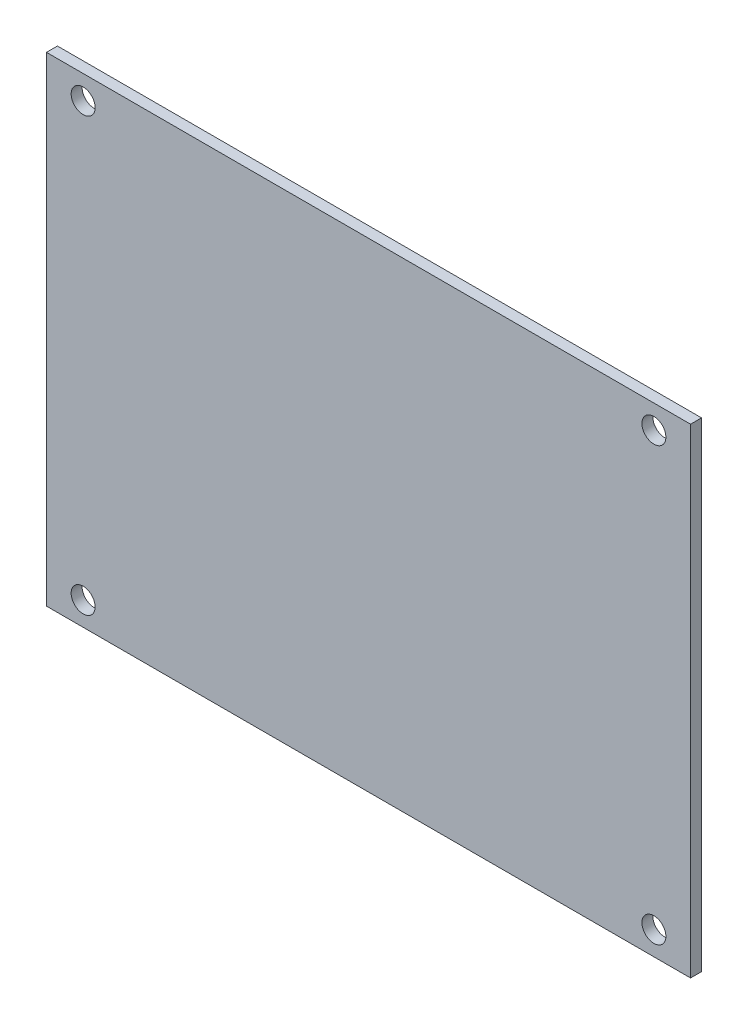
SolidWorks part; units mm, degrees
ref_plane "Front Plane" through (0, 0, 0) normal (0, 0, 1) x (1, 0, 0)
ref_plane "Top Plane" through (0, 0, 0) normal (0, 1, 0) x (1, 0, 0)
ref_plane "Right Plane" through (0, 0, 0) normal (1, 0, 0) x (0, 0, -1)
sketch "Sketch1" plane through (0, 0, 0) normal (0, 0, 1) x (1, 0, 0)
  line L0 (0, 35) -> (0, -35) construction
  line L1 (-47, -35) -> (47, -35)
  line L2 (-47, -35) -> (-47, 35)
  line L3 (-47, 35) -> (47, 35)
  line L4 (47, -35) -> (47, 35)
  line L5 (-47, -35) -> (47, 35) construction
  line L6 (-47, 35) -> (47, -35) construction
  line L7 (-47, 0) -> (47, 0) construction
  circle A0 centre (-41.65, 31.55) radius 1.75
  circle A1 centre (41.65, 31.55) radius 1.75
  circle A2 centre (41.65, -31.55) radius 1.75
  circle A3 centre (-41.65, -31.55) radius 1.75
  point P0 (0, 0)
  dimension "D3" = 3.5
  dimension "D4" = 3.6
  dimension "D5" = 1.7
  dimension "D1" = 94
  dimension "D2" = 70
extrude "Boss-Extrude1" add sketch "Sketch1" along normal blind 1.6
